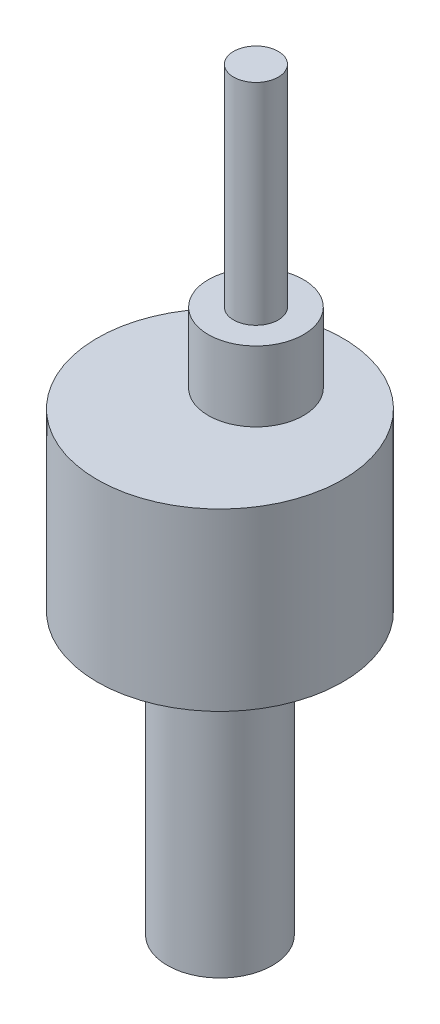
SolidWorks part; units mm, degrees
ref_plane "Front Plane" through (0, 0, 0) normal (0, 0, 1) x (1, 0, 0)
ref_plane "Top Plane" through (0, 0, 0) normal (0, 1, 0) x (1, 0, 0)
ref_plane "Right Plane" through (0, 0, 0) normal (1, 0, 0) x (0, 0, -1)
sketch "Sketch1" plane through (0, 0, 0) normal (0, 1, 0) x (1, 0, 0)
  circle A0 centre (0, 0) radius 22.5
  dimension "D1" = 45
extrude "Boss-Extrude1" add sketch "Sketch1" along normal blind 120
sketch "Sketch2" plane through (0, 120, 0) normal (0, 1, 0) x (1, 0, 0)
  circle A0 centre (0, 0) radius 52.5
  dimension "D1" = 105
extrude "Boss-Extrude2" add sketch "Sketch2" along normal blind 75
sketch "Sketch3" plane through (0, 195, 0) normal (0, 1, 0) x (1, 0, 0)
  circle A0 centre (0, 15.4068) radius 20.3822
  dimension "D1" = 40.7643
extrude "Boss-Extrude3" add sketch "Sketch3" along normal blind 30
sketch "Sketch4" plane through (0, 225, 0) normal (0, 1, 0) x (1, 0, 0)
  circle A0 centre (0, 15.4068) radius 9.5541
  dimension "D1" = 19.1083
extrude "Boss-Extrude4" add sketch "Sketch4" along normal blind 90
